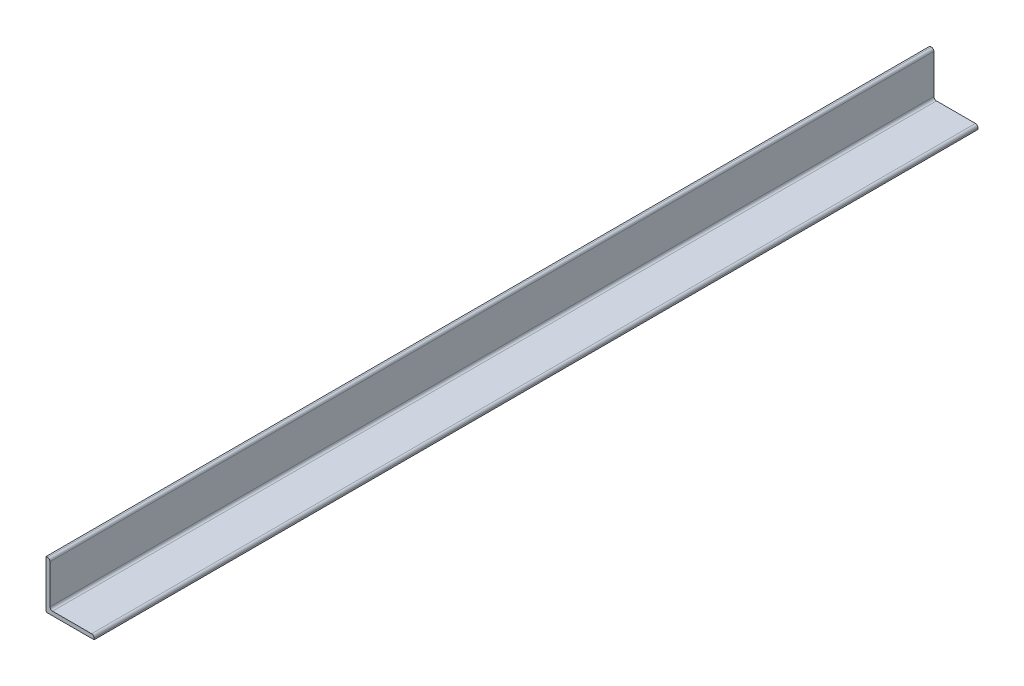
SolidWorks part; units mm, degrees
ref_plane "Front Plane" through (0, 0, 0) normal (0, 0, 1) x (1, 0, 0)
ref_plane "Top Plane" through (0, 0, 0) normal (0, 1, 0) x (1, 0, 0)
ref_plane "Right Plane" through (0, 0, 0) normal (1, 0, 0) x (0, 0, -1)
sketch "Sketch1" plane through (0, 0, 0) normal (0, 0, 1) x (1, 0, 0)
  line L0 (0, 0) -> (0, 19.05)
  line L1 (0, 19.05) -> (1.5875, 19.05)
  line L2 (1.5875, 19.05) -> (1.5875, 1.5875)
  line L3 (1.5875, 1.5875) -> (19.05, 1.5875)
  line L4 (19.05, 1.5875) -> (19.05, 0)
  line L5 (19.05, 0) -> (0, 0)
  dimension "D1" = 1.5875
  dimension "D2" = 19.05
extrude "Boss-Extrude1" add sketch "Sketch1" along normal blind 350
fillet "Fillet1" radius 1 3 edges at (19.05, 1.5875, 175) (1.5875, 1.5875, 175) (1.5875, 19.05, 175)
fillet "Fillet2" radius 0.5 1 edges at (0, 0, 175)
ref_plane "Plane1" through (0, 0, 175) normal (0, 0, 1) x (1, 0, 0)
